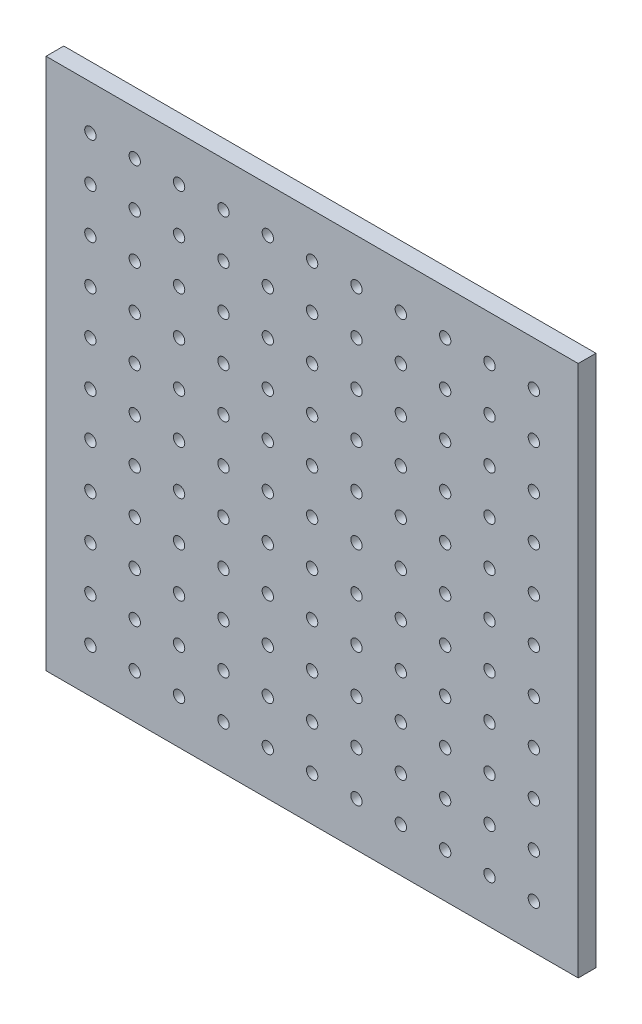
SolidWorks part; units mm, degrees
ref_plane "정면" through (0, 0, 0) normal (0, 0, 1) x (1, 0, 0)
ref_plane "윗면" through (0, 0, 0) normal (0, 1, 0) x (1, 0, 0)
ref_plane "우측면" through (0, 0, 0) normal (1, 0, 0) x (0, 0, -1)
sketch "스케치1" plane through (0, 0, 0) normal (0, 0, 1) x (1, 0, 0)
  line L1 (150, -150) -> (-150, -150)
  line L2 (150, -150) -> (150, 150)
  line L3 (150, 150) -> (-150, 150)
  line L4 (-150, -150) -> (-150, 150)
  line L5 (150, -150) -> (-150, 150) construction
  line L6 (150, 150) -> (-150, -150) construction
  point P0 (0, 0)
  dimension "D1" = 300
  dimension "D2" = 300
extrude "보스-돌출1" add sketch "스케치1" along normal blind 10
sketch "스케치2" plane through (0, 0, 10) normal (0, 0, 1) x (1, 0, 0)
  line L0 (-150, 150) -> (-150, -150) construction
  line L1 (150, 150) -> (-150, 150) construction
  circle A0 centre (-125, 125) radius 3.2
  dimension "D1" = 6.4
  dimension "D2" = 25
  dimension "D3" = 25
extrude "컷-돌출1" cut sketch "스케치2" against normal through all
pattern_linear "선형 패턴1" count 11 spacing 25 along (1, 0, 0) of "컷-돌출1"
pattern_linear "선형 패턴2" count 11 spacing 25 along (0, -1, 0) of "선형 패턴1", "컷-돌출1"
